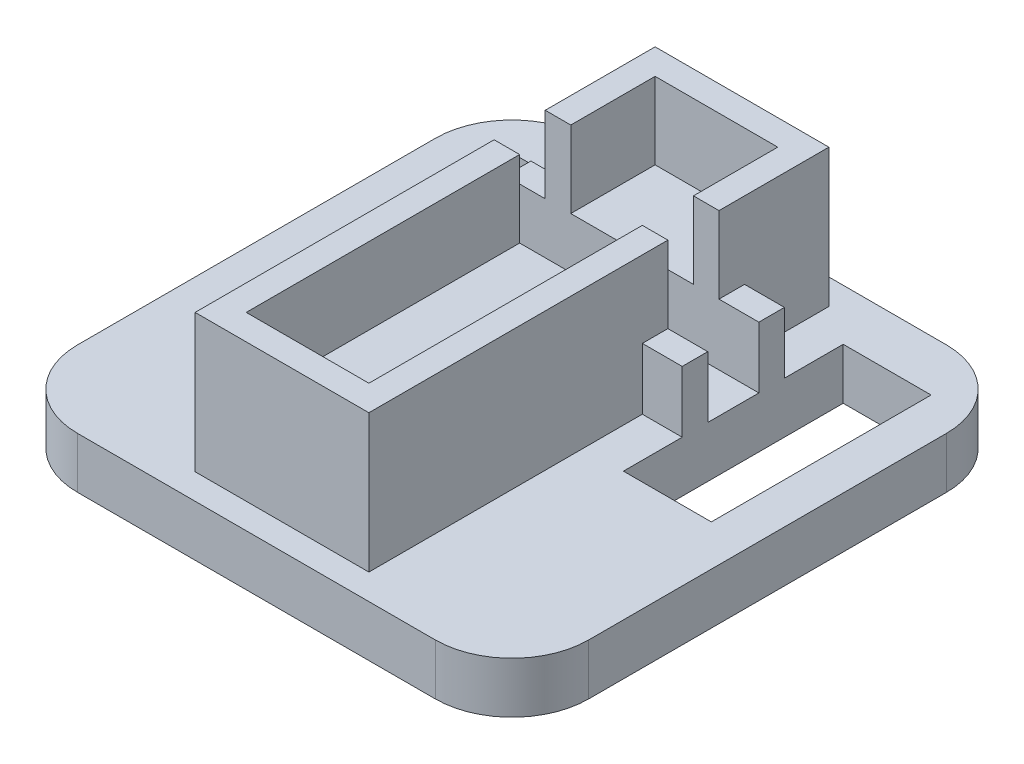
SolidWorks part; units mm, degrees
ref_plane "Front Plane" through (0, 0, 0) normal (0, 0, 1) x (1, 0, 0)
ref_plane "Top Plane" through (0, 0, 0) normal (0, 1, 0) x (1, 0, 0)
ref_plane "Right Plane" through (0, 0, 0) normal (1, 0, 0) x (0, 0, -1)
sketch "Sketch1" plane through (0, 0, 0) normal (0, 1, 0) x (1, 0, 0)
  line L0 (-35, 50) -> (35, 50)
  line L5 (-50, 35) -> (-50, -35)
  line L6 (50, 35) -> (50, -35)
  line L7 (-35, -50) -> (35, -50)
  line L8 (-50, 0) -> (50, 0) construction
  line L9 (0, -50) -> (0, 50) construction
  arc A0 (50, -35) -> (35, -50) centre (35, -35) cw
  arc A1 (-50, -35) -> (-35, -50) centre (-35, -35) ccw
  arc A2 (-35, 50) -> (-50, 35) centre (-35, 35) ccw
  arc A3 (35, 50) -> (50, 35) centre (35, 35) cw
  point P12 (0, -50)
  point P18 (0, 0)
  point P19 (0, 0)
  dimension "D3" = 70
  dimension "D1" = 100
  dimension "D2" = 100
extrude "Boss-Extrude1" add sketch "Sketch1" along normal blind 10
sketch "Sketch3" plane through (0, 10, 0) normal (0, 1, 0) x (1, 0, 0)
  line L1 (-24.8, 40) -> (-42, 40)
  line L2 (-24.8, 40) -> (-24.8, -3)
  line L3 (-24.8, -3) -> (-42, -3)
  line L4 (-42, 40) -> (-42, -3)
  line L5 (24.8, 40) -> (42, 40)
  line L6 (24.8, 40) -> (24.8, -3)
  line L7 (24.8, -3) -> (42, -3)
  line L8 (42, 40) -> (42, -3)
  line L9 (-50, 35) -> (-50, -35) construction
  line L10 (50, -35) -> (50, 35) construction
  line L12 (35, 50) -> (-35, 50) construction
  dimension "D1" = 17.2
  dimension "D2" = 17.2
  dimension "D3" = 43
  dimension "D4" = 43
  dimension "D5" = 8
  dimension "D6" = 8
  dimension "D7" = 10
  dimension "D8" = 10
extrude "Cut-Extrude1" cut sketch "Sketch3" against normal through all
sketch "Sketch5" plane through (0, 10, 0) normal (0, 1, 0) x (1, 0, 0)
  line L0 (42, 18.5) -> (-42, 18.5) construction
  line L1 (42, -3) -> (42, 40) construction
  line L2 (-42, 40) -> (-42, -3) construction
  line L3 (24.8, 40) -> (24.8, -3) construction
  line L4 (-24.8, 23.5) -> (24.8, 23.5)
  line L6 (-24.8, 13.5) -> (24.8, 13.5)
  line L11 (24.8, 13.5) -> (-24.8, 13.5)
  line L12 (24.8, 13.5) -> (24.8, 8.5)
  line L13 (24.8, 8.5) -> (-24.8, 8.5)
  line L14 (-24.8, 13.5) -> (-24.8, 8.5)
  line L16 (-24.8, -3) -> (-24.8, 40) construction
  line L17 (24.8, 23.5) -> (-24.8, 23.5)
  line L18 (24.8, 23.5) -> (24.8, 28.5)
  line L19 (24.8, 28.5) -> (-24.8, 28.5)
  line L20 (-24.8, 23.5) -> (-24.8, 28.5)
  point P6 (0, 18.5)
  point P19 (0, 0)
  point P20 (0, 0)
  line M5 (-24.8, 40) -> (-24.8, -3)
  line M9 (24.8, -3) -> (24.8, 40)
  dimension "D1" = 10
  dimension "D2" = 5
  dimension "D3" = 5
  dimension "D4" = 10
  dimension "D5" = 5
extrude "Boss-Extrude3" add sketch "Sketch5" along normal blind 12 contours L13 L6 M9 M5 | L19 L4 M9 M5
sketch "Sketch2" plane through (0, 22, 0) normal (0, 1, 0) x (1, 0, 0)
  line L1 (-12, 40) -> (12, 40)
  line L2 (-12, 40) -> (-12, -40)
  line L3 (-12, -40) -> (12, -40)
  line L4 (12, 40) -> (12, -40)
  line L5 (-12, 40) -> (12, -40) construction
  line L6 (-12, -40) -> (12, 40) construction
  line L7 (-17, 45) -> (17, 45)
  line L8 (-17, 45) -> (-17, -45)
  line L9 (-17, -45) -> (17, -45)
  line L10 (17, 45) -> (17, -45)
  line L11 (-17, 45) -> (17, -45) construction
  line L12 (-17, -45) -> (17, 45) construction
  point P0 (0, 0)
  point P6 (0, 0)
  point P11 (0, 40)
  dimension "D1" = 24
  dimension "D2" = 80
  dimension "D3" = 5
  dimension "D4" = 5
extrude "Boss-Extrude2" add sketch "Sketch2" along normal blind 15 and the other way up to body separate body
sketch "Sketch6" plane through (0, 37, 0) normal (0, 1, 0) x (1, 0, 0)
  line L0 (17, -45) -> (17, 45) construction
  line L2 (-17, 45) -> (-17, -45) construction
  line L3 (-17, -45) -> (17, -45) construction
  line L6 (-12, 13.5) -> (12, 13.5) construction
  line L9 (-12, 23.5) -> (12, 23.5) construction
  line L11 (-12, 13.5) -> (12, 13.5) construction
  line L12 (-12, 23.5) -> (12, 23.5) construction
  line L28 (17, 13.5) -> (17, 23.5)
  line L30 (-17, 23.5) -> (-17, 13.5)
  line L31 (-17, -45) -> (17, -45)
  line L56 (-12, 23.5) -> (-17, 23.5)
  line L57 (-17, 13.5) -> (-12, 13.5)
  line L58 (-12, 23.5) -> (-12, 13.5)
  line L59 (12, 23.5) -> (17, 23.5)
  line L60 (12, 13.5) -> (17, 13.5)
  line L61 (12, 23.5) -> (12, 13.5)
  point P2 (0, 0)
  point P4 (0, 0)
  point P6 (0, 0)
  point P7 (0, 0)
  point P8 (0, 0)
  point P10 (0, 0)
  point P11 (0, 0)
  point P12 (0, 0)
  line M37 (17, -45) -> (17, 45)
  line M39 (-17, 45) -> (-17, -45)
  line M42 (12, 40) -> (12, -40)
  line M44 (-12, -40) -> (-12, 40)
  dimension "D1" = 5
  dimension "D2" = 5
  dimension "D3" = 10
  dimension "D4" = 10
extrude "Cut-Extrude2" cut sketch "Sketch6" against normal up to surface (27 mm away) contours L57 L56 M39 M44 | L60 L59 M42 M37 up to face at (0, 10, 0)
sketch "Sketch8" plane through (0, 10, 0) normal (0, 1, 0) x (1, 0, 0)
  line L4 (12, -40) -> (12, 8.5)
  line L5 (12, 8.5) -> (-12, 8.5)
  line L6 (-12, 8.5) -> (-12, -40)
  line L7 (-12, -40) -> (12, -40)
  line L8 (12, -40) -> (12, 8.5)
  line L9 (12, 8.5) -> (-12, 8.5)
  line L10 (-12, 8.5) -> (-12, -40)
  line L11 (-12, -40) -> (12, -40)
  line L12 (12, 28.5) -> (12, 40)
  line L13 (12, 40) -> (-12, 40)
  line L14 (-12, 40) -> (-12, 28.5)
  line L15 (-12, 28.5) -> (12, 28.5)
  line L16 (12, 28.5) -> (12, 40)
  line L17 (12, 40) -> (-12, 40)
  line L18 (-12, 40) -> (-12, 28.5)
  line L19 (-12, 28.5) -> (12, 28.5)
  dimension "D1" = 0
  dimension "D2" = 0
extrude "Boss-Extrude4" add sketch "Sketch8" along normal up to surface (12 mm away) up to face at (0, 22, -11)
